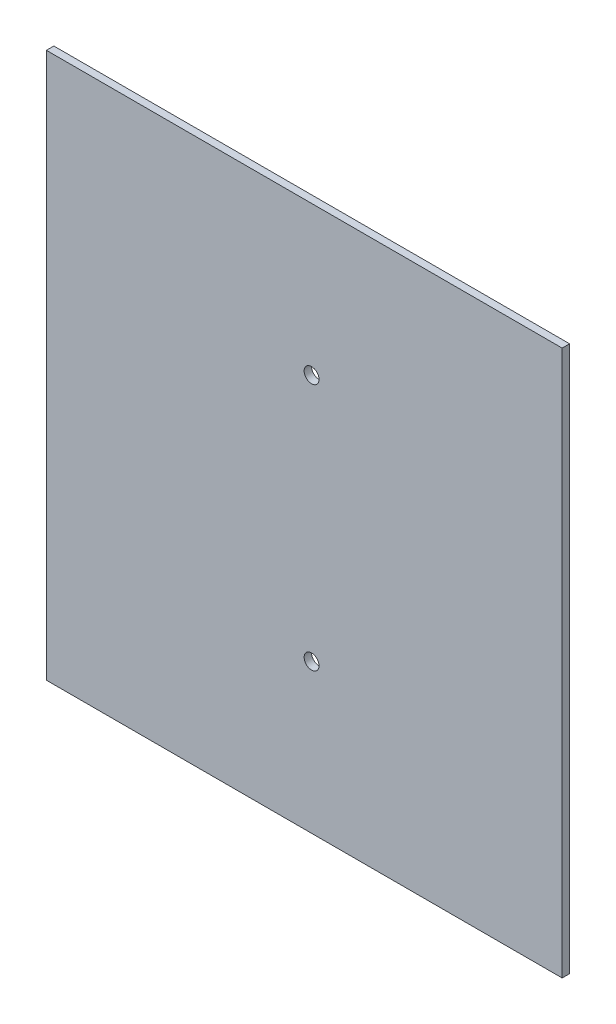
SolidWorks part; units mm, degrees
ref_plane "Front Plane" through (0, 0, 0) normal (0, 0, 1) x (1, 0, 0)
ref_plane "Top Plane" through (0, 0, 0) normal (0, 1, 0) x (1, 0, 0)
ref_plane "Right Plane" through (0, 0, 0) normal (1, 0, 0) x (0, 0, -1)
sketch "Sketch2" plane through (0, 0, 0) normal (0, 0, 1) x (1, 0, 0)
  line L1 (0, 0) -> (104, 0)
  line L2 (0, 0) -> (0, 110)
  line L3 (0, 110) -> (104, 110)
  line L4 (104, 0) -> (104, 110)
  dimension "D1" = 110
  dimension "D2" = 104
extrude "Boss-Extrude1" add sketch "Sketch2" along normal blind 1.5 contours L3 L4 L1 L2
hole_wizard "Ø3.0mm Dowel Hole2" positions "Sketch5" profile "Sketch6" hole size "Ø3.0" standard "ANSI Metric" end condition through all
sketch "Sketch5" plane through (34.2341, -1.12, -1.5) normal (0, 0, -1) x (-1, 0, 0)
  point P0 (-19.2379, 81.12)
  point P2 (-19.2379, 31.12)
sketch "Sketch6" plane through (53.4721, 80, -1.5) normal (1, 0, 0) x (0, 1, 0)
  line L0 (0, 0) -> (0, 3)
  line L1 (0, 3) -> (1.5, 3)
  line L2 (1.5, 3) -> (1.5, 0)
  line L3 (1.5, 0) -> (0, 0)
  line L4 (0, -6.35) -> (0, 107.95) construction
  dimension "Thru Hole Dia." = 3
  dimension "Thru Hole Depth" = 3
